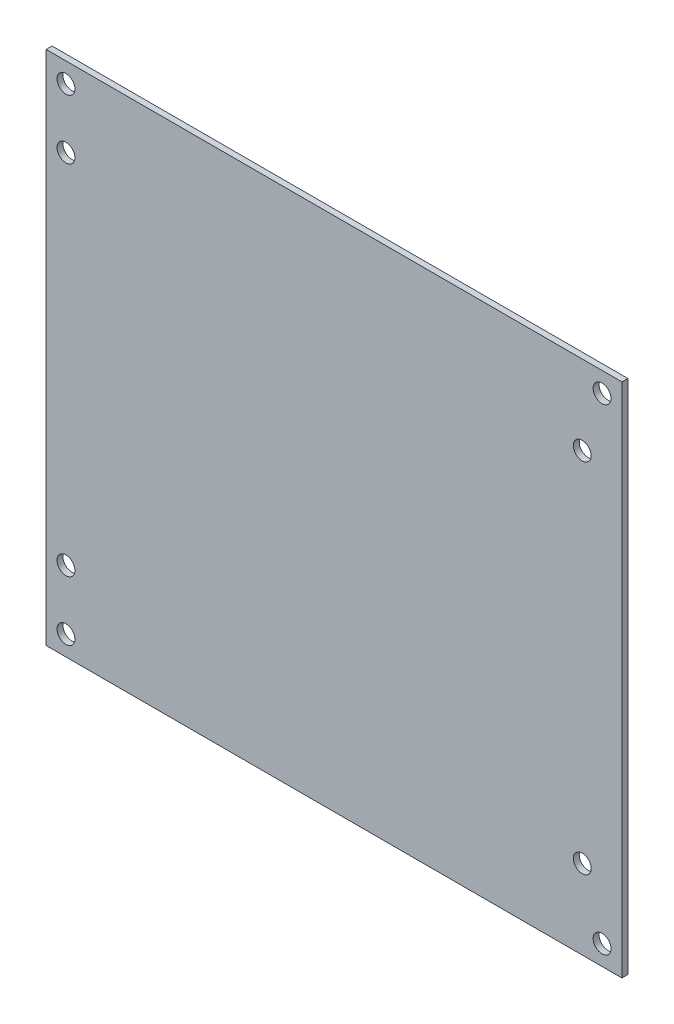
SolidWorks part; units mm, degrees
ref_plane "Спереди" through (0, 0, 0) normal (0, 0, 1) x (1, 0, 0)
ref_plane "Сверху" through (0, 0, 0) normal (0, 1, 0) x (1, 0, 0)
ref_plane "Справа" through (0, 0, 0) normal (1, 0, 0) x (0, 0, -1)
sketch "Эскиз1" plane through (0, 0, 0) normal (0, 0, 1) x (1, 0, 0)
  line L0 (0, 42.3611) -> (0, -41.9385) construction
  line L1 (-56.8336, 0) -> (57.0449, 0) construction
  line L2 (62.5, -45) -> (62.5, 45) construction
  line L3 (-72.5, -65) -> (72.5, -65)
  line L4 (-72.5, -65) -> (-72.5, 65)
  line L5 (-72.5, 65) -> (72.5, 65)
  line L6 (72.5, -65) -> (72.5, 65)
  circle A0 centre (-67.5, 60) radius 2.25
  circle A1 centre (-67.5, -60) radius 2.25
  circle A2 centre (67.5, -60) radius 2.25
  circle A3 centre (67.5, 60) radius 2.25
  circle A4 centre (-67.5, 45) radius 2.25
  circle A5 centre (-67.5, -45) radius 2.25
  circle A6 centre (62.5, 45) radius 2.25
  circle A7 centre (62.5, -45) radius 2.25
  dimension "D3" = 5
  dimension "D5" = 4.5
  dimension "D8" = 4.5
  dimension "D10" = 90
  dimension "D1" = 145
  dimension "D2" = 130
  dimension "D4" = 5
  dimension "D6" = 5
  dimension "D7" = 45
  dimension "D9" = 10
extrude "Вытянуть1" add sketch "Эскиз1" along normal blind 1.5
